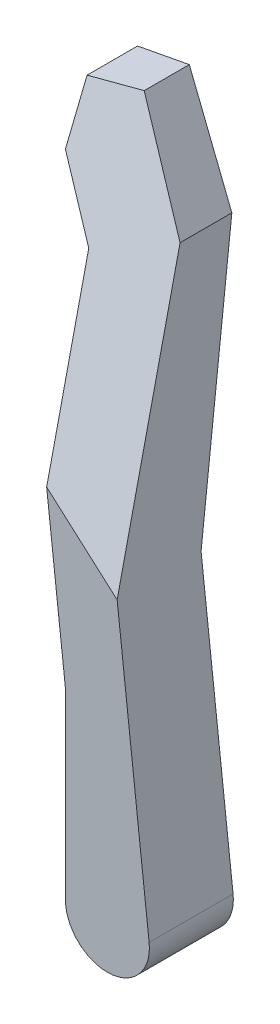
SolidWorks part; units mm, degrees
material "POM 乙缩醛共聚物"
ref_plane "前视基准面" through (0, 0, 0) normal (0, 0, 1) x (1, 0, 0)
ref_plane "上视基准面" through (0, 0, 0) normal (0, 1, 0) x (1, 0, 0)
ref_plane "右视基准面" through (0, 0, 0) normal (1, 0, 0) x (0, 0, -1)
other "Configuration Table"
sketch "草图2" plane through (0, 0, 0) normal (0, 0, 1) x (1, 0, 0)
  line L0 (3.9743, 0.4528) -> (-1.7802, 50.959)
  line L1 (-1.7802, 50.959) -> (-7, 60)
  line L2 (-7, 60) -> (-11, 60)
  line L3 (-11, 60) -> (-11, 54.9282)
  line L4 (-11, 54.9282) -> (-7.6003, 49.0398)
  line L5 (-7.6003, 49.0398) -> (-4, 17.4402)
  line L6 (-4, 17.4402) -> (-4, 0)
  arc A0 (-4, 0) -> (3.9743, 0.4528) centre (0, 0) ccw
  dimension "D4" = 4
  dimension "D1" = 4
  dimension "D2" = 4
  dimension "D3" = 6
  dimension "D5" = 30
  dimension "D6" = 11
  dimension "D7" = 6
  dimension "D8" = 6.5
  dimension "D9" = 60
extrude "凸台-拉伸1" add sketch "草图2" against normal blind 8 from offset 3 offset against normal yes
sketch "草图4" plane through (0, 0, -11) normal (0, 0, -1) x (-1, 0, 0)
  line L0 (-0.9267, 27.2011) -> (5.7891, 33.1427)
  line L7 (4, 0) -> (4, 17.4402)
  line L8 (4, 17.4402) -> (7.6003, 49.0398)
  line L9 (7.6003, 49.0398) -> (11, 54.9282)
  line L10 (11, 54.9282) -> (11, 60)
  line L11 (11, 60) -> (7, 60)
  line L12 (7, 60) -> (1.7802, 50.959)
  line L13 (1.7802, 50.959) -> (-3.9743, 0.4528)
  line L14 (4, 0) -> (4, 17.4402)
  line L15 (4, 17.4402) -> (7.6003, 49.0398)
  line L16 (7.6003, 49.0398) -> (11, 54.9282)
  line L17 (11, 54.9282) -> (11, 60)
  line L18 (11, 60) -> (7, 60)
  line L19 (7, 60) -> (1.7802, 50.959)
  line L20 (1.7802, 50.959) -> (-3.9743, 0.4528)
  arc A1 (-3.9743, 0.4528) -> (4, 0) centre (0, 0) ccw
  arc A2 (-3.9743, 0.4528) -> (4, 0) centre (0, 0) ccw
  line M11 (4, 17.4402) -> (7.6003, 49.0398)
  line M12 (7.6003, 49.0398) -> (11, 54.9282)
  line M13 (11, 54.9282) -> (11, 60)
  line M14 (11, 60) -> (7, 60)
  line M15 (7, 60) -> (1.7802, 50.959)
  line M16 (1.7802, 50.959) -> (-3.9743, 0.4528)
  dimension "D2" = 42
  dimension "D3" = 16
  dimension "D1" = 0
extrude "凸台-拉伸2" add sketch "草图4" along normal blind 8 contours L0 M16 M11 M12 M13 M14 M15
sketch "草图5" plane through (3.9743, 0.4528, 0) normal (0.9936, 0.1132, 0) x (0, 0, -1)
  line L0 (11, 26.9213) -> (19, 60.8595)
  line L1 (19, 60.8595) -> (19, 26.9213)
  line L2 (19, 26.9213) -> (11, 26.9213) construction
  line L3 (19, 26.9213) -> (11, 26.9213)
  line L4 (19, 50.8329) -> (19, 26.9213) construction
  line L5 (15.3525, 60.8595) -> (3, 26.9213)
  line L7 (3, 0) -> (3, 50.8329) construction
  line L8 (3, 26.9213) -> (3, 60.8595)
  line L9 (3, 60.8595) -> (15.3525, 60.8595)
  line L10 (19, 60.8595) -> (3, 60.8595) construction
  dimension "D1" = 8
  dimension "D2" = 20
extrude "切除-拉伸2" cut sketch "草图5" along direction (-0.749, 0.6626, 0) on the side against the normal through all
